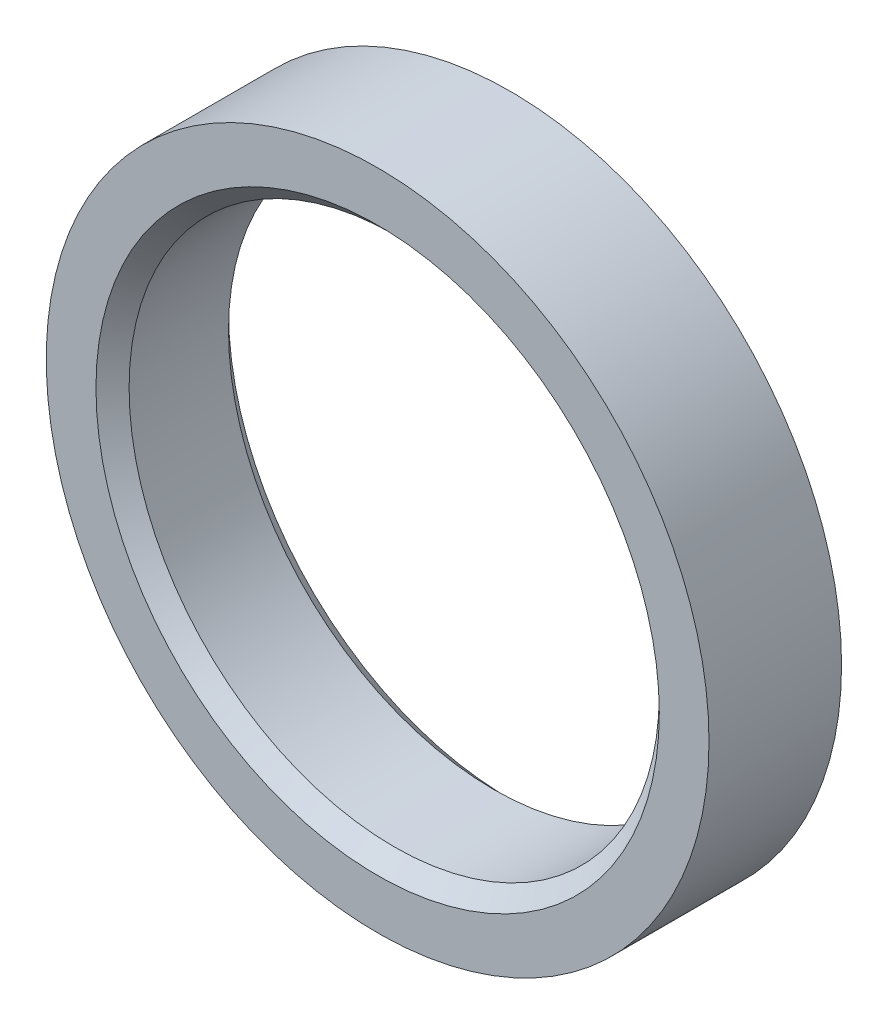
SolidWorks part; units mm, degrees
ref_plane "Piano frontale" through (0, 0, 0) normal (0, 0, 1) x (1, 0, 0)
ref_plane "Piano superiore" through (0, 0, 0) normal (0, 1, 0) x (1, 0, 0)
ref_plane "Piano destro" through (0, 0, 0) normal (1, 0, 0) x (0, 0, -1)
sketch "Schizzo1" plane through (0, 0, 0) normal (0, 0, 1) x (1, 0, 0)
  circle A0 centre (0, 0) radius 20
  circle A1 centre (0, 0) radius 16
  dimension "D1" = 32
  dimension "20" = 40
extrude "Estrusione-Estrusione1" add sketch "Schizzo1" along normal blind 8
chamfer "Smusso2" distance 1 angle 45 2 edges at (16, 0, 0) (16, 0, 8)
